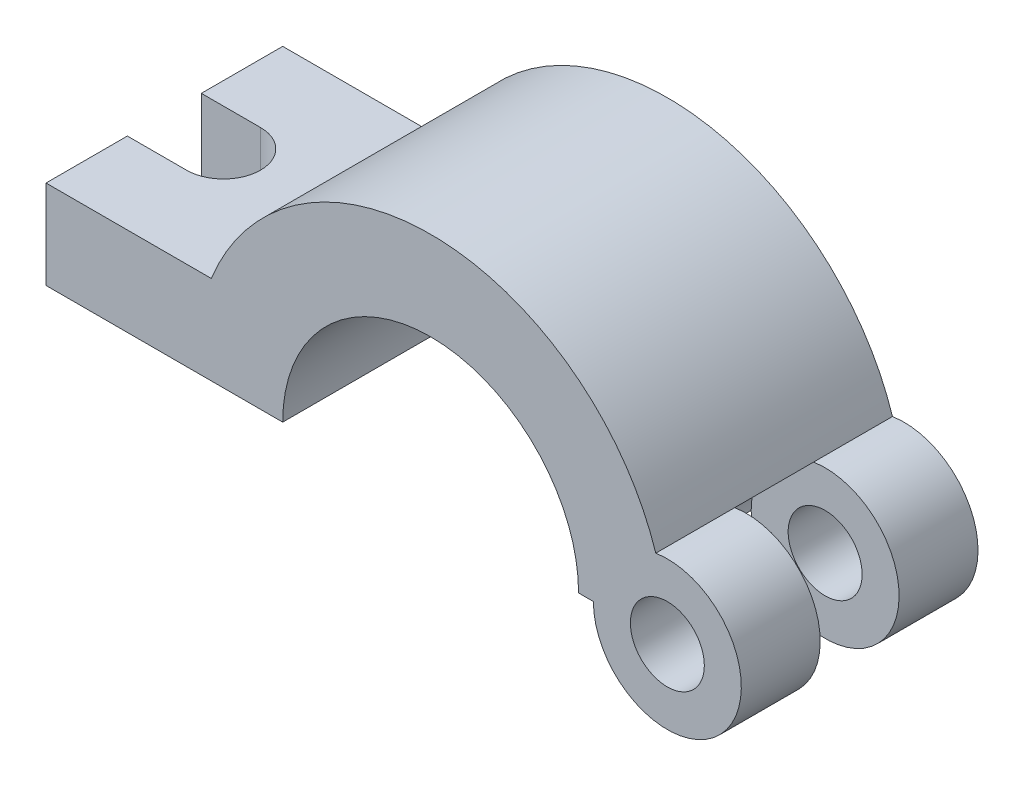
SolidWorks part; units mm, degrees
ref_plane "Front Plane" through (0, 0, 0) normal (0, 0, 1) x (1, 0, 0)
ref_plane "Top Plane" through (0, 0, 0) normal (0, 1, 0) x (1, 0, 0)
ref_plane "Right Plane" through (0, 0, 0) normal (1, 0, 0) x (0, 0, -1)
sketch "Sketch1" plane through (0, 0, 0) normal (0, 0, 1) x (1, 0, 0)
  line L0 (55, 0) -> (-55, 0) construction
  line L2 (-8, 0) -> (-13, 0)
  line L3 (-13, 0) -> (-13, 3)
  line L4 (-13, 3) -> (-7.4162, 3)
  line L5 (5, 0) -> (8, 0)
  line L6 (-8, 0) -> (-5, 0)
  arc A0 (-5, 0) -> (5, 0) centre (0, 0) cw
  arc A1 (-8, 0) -> (8, 0) centre (0, 0) cw
  dimension "D1" = 5
  dimension "D2" = 8
  dimension "D3" = 5
  dimension "D4" = 3
extrude "Boss-Extrude1" add sketch "Sketch1" along normal mid plane 8 contours A1 L6 A0 L5 | L2 A1 L4 L3
sketch "Sketch2" plane through (0, 0, 0) normal (0, 0, 1) x (1, 0, 0)
  line L0 (55, 0) -> (-55, 0) construction
  circle A0 centre (8, 0) radius 2.5
  arc A1 (8, 0) -> (-7.4162, 3) centre (0, 0) ccw construction
  dimension "D1" = 5
extrude "Boss-Extrude3" add sketch "Sketch2" along normal mid plane 8
sketch "Sketch3" plane through (0, 0, 4) normal (0, 0, 1) x (1, 0, 0)
  line L0 (55, 0) -> (-55, 0) construction
  circle A0 centre (8, 0) radius 1.25
  arc A1 (5.5, 0) -> (7.6094, 2.4693) centre (8, 0) ccw construction
  dimension "D1" = 2.5
  dimension "D2" = 0
extrude "Cut-Extrude1" cut sketch "Sketch3" against normal up to surface (8 mm away) up to face at (-2.3964, 2.2673, -4)
sketch "Sketch4" plane through (0, 0, 0) normal (0, 0, 1) x (1, 0, 0)
  circle A0 centre (8, 0) radius 2.5
  dimension "D1" = 5
extrude "Cut-Extrude2" cut sketch "Sketch4" against normal mid plane 2.6667
sketch "Sketch5" plane through (0, 3, 0) normal (0, 1, 0) x (1, 0, 0)
  line L0 (-13, 1.25) -> (-11, 1.25)
  line L1 (-13, -4) -> (-13, 4) construction
  line L2 (-13, -1.25) -> (-11, -1.25)
  line L3 (-44.2539, 0) -> (44.2539, 0) construction
  arc A0 (-11, 1.25) -> (-11, -1.25) centre (-11, 0) cw
  dimension "D1" = 1.25
  dimension "D2" = 0
  dimension "D3" = 2
extrude "Cut-Extrude3" cut sketch "Sketch5" along direction (0, 1, 0) on the side against the normal blind 3 and the other way through all
equation "\"InnerRad\"= 5"
equation "\"D1@Sketch1\"=\"InnerRad\""
equation "\"D2@Sketch1\"=\"InnerRad\"+3"
equation "\"depth\"=8"
equation "\"D1@Boss-Extrude1\"=\"depth\""
equation "\"D1@Boss-Extrude3\"=\"depth\""
equation "\"D1@Cut-Extrude2\"=\"depth\"/3"
